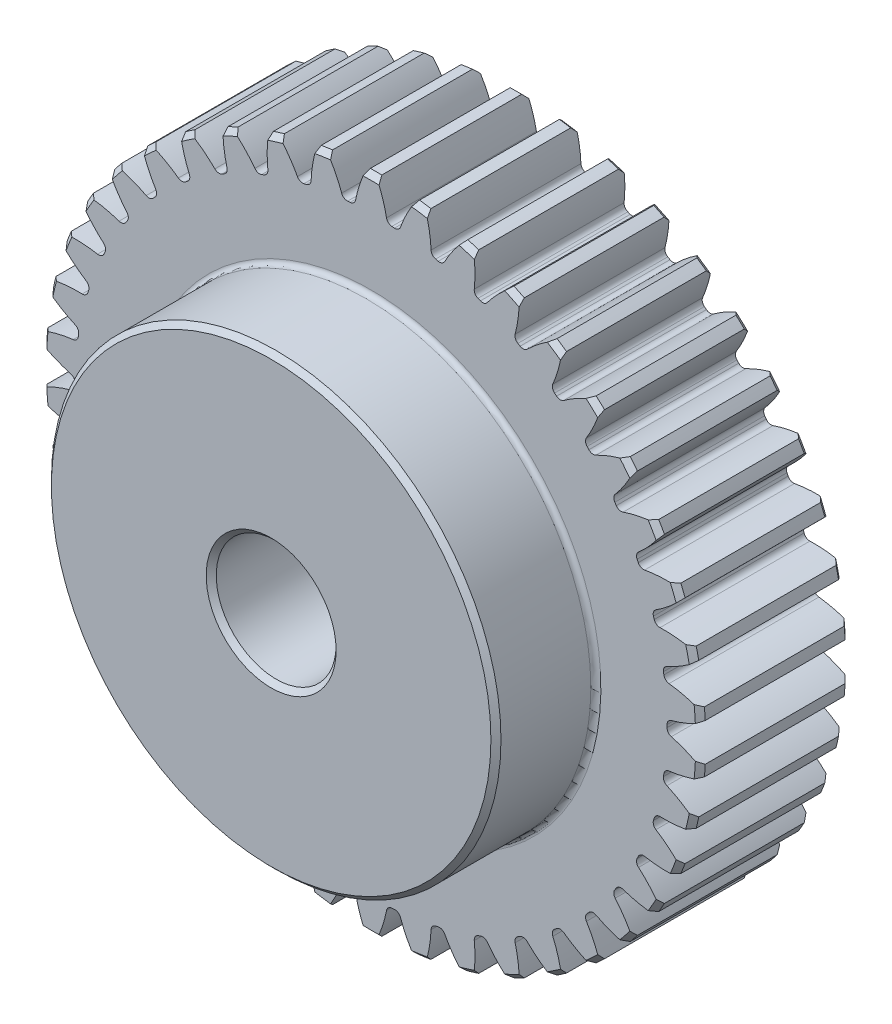
SolidWorks part; units mm, degrees
ref_plane "Front Plane" through (0, 0, 0) normal (0, 0, 1) x (1, 0, 0)
ref_plane "Top Plane" through (0, 0, 0) normal (0, 1, 0) x (1, 0, 0)
ref_plane "Right Plane" through (0, 0, 0) normal (1, 0, 0) x (0, 0, -1)
sketch "Sketch1" plane through (0, 0, 0) normal (0, 0, 1) x (1, 0, 0)
  line L0 (0, 0) -> (0, 31.5) construction
  line L1 (-10.1239, 35.1848) -> (10.1239, 27.8152) construction
  circle A0 centre (0, 0) radius 29.625 construction
  circle A1 centre (0, 0) radius 33 construction
  circle A2 centre (0, 0) radius 31.5 construction
  circle A3 centre (0, 0) radius 29.6003 construction
  circle A4 centre (0, 0) radius 22.5 construction
  circle A5 centre (0, 0) radius 6 construction
  point P8 (0.75, 0)
  point P13 (21, 0)
  dimension "OD" = 66
  dimension "Root Diameter" = 59.25
  dimension "Gear Pitch Diameter" = 63
  dimension "Base Diameter" = 59.2006
  dimension "Hub Diameter" = 45
  dimension "For Shaft Diameter" = 12
  dimension "Pressure Angle" = 20
  dimension "Number of Teeth" = 42
  dimension "Module" = 1.5
sketch "Sketch2" plane through (0, 0, 0) normal (1, 0, 0) x (0, 0, -1)
  line L0 (-10, 0) -> (15, 0) construction
  line L1 (15, 33) -> (15, -33) construction
  line L2 (0, -22.5) -> (-10, -22.5) construction
  line L3 (-10, 33) -> (15, 33) construction
  line L8 (-10, -22.5) -> (-10, 22.5) construction
  point P4 (0, 33)
  point P5 (-5, 0)
  dimension "Overall Width" = 25
  dimension "Hub Width" = 10
  dimension "Approx Set Screw Positon" = 5
  dimension "Face Width" = 15
sketch "Sketch3" plane through (0, 0, 0) normal (0, 0, 1) x (1, 0, 0)
  circle A0 centre (0, 0) radius 33
  circle A1 centre (0, 0) radius 33 construction
extrude "Boss-Extrude1" add sketch "Sketch3" against normal up to vertex (15 mm away) and the other way up to vertex (10 mm away) up to point (0, 0, -15) other way up to point (0, 0, 10)
sketch "Sketch5" plane through (0, 0, 0) normal (1, 0, 0) x (0, 0, -1)
  line L1 (0, 22.5) -> (-10, 22.5)
  line L2 (0, 22.5) -> (0, 33)
  line L3 (0, 33) -> (-10, 33)
  line L4 (-10, 22.5) -> (-10, 33)
  line L5 (-10, 0) -> (15, 0)
  line L6 (-10, 0) -> (-10, 6)
  line L7 (-10, 6) -> (15, 6)
  line L8 (15, 0) -> (15, 6)
  point P5 (0, 22.5)
  point P12 (0, 6)
revolve "Cut-Revolve1" cut sketch "Sketch5" angle 360 about L0
fillet "Fillet2" radius 0.5033 1 edges at (0, -22.5, 0)
chamfer "Chamfer1" distance 0.5033 angle 45 5 edges at (0, -6, -15) (0, -33, 0) (33, 0, -15) (0, -6, 10) (0, -22.5, 10)
sketch "Sketch4" plane through (0, 0, 0) normal (0, 0, 1) x (1, 0, 0)
  line L0 (29.6191, 0.589) -> (29.6191, -0.589)
  arc A3 (32.9456, 1.8943) -> (32.9456, -1.8943) centre (0, 0) cw
  circle A4 centre (0, 0) radius 33 construction
  arc A5 (29.6191, 0.589) -> (32.9456, 1.8943) centre (26.6987, 12.9235) ccw
  circle A8 centre (0, 0) radius 29.625 construction
  arc A9 (29.6191, -0.589) -> (32.9456, -1.8943) centre (26.6987, -12.9235) cw
  spline S0 degree 4 poles (29.5928, 0.6658) (29.5981, 0.666) (29.613, 0.6667) (29.6412, 0.6686) (29.6871, 0.6727) (29.7455, 0.6794) (29.821, 0.6896) (29.9098, 0.7037) (30.0073, 0.7214) (30.1132, 0.7431) (30.2188, 0.7668) (30.324, 0.7924) (30.4286, 0.8196) (30.5553, 0.8547) (30.707, 0.8996) (30.8839, 0.9564) (31.0842, 1.0257) (31.2878, 1.1016) (31.4878, 1.1807) (31.6893, 1.2656) (31.884, 1.3514) (32.0857, 1.4455) (32.2716, 1.5351) (32.4792, 1.6411) (32.6466, 1.7283) (32.8667, 1.8494) (32.9965, 1.9227) (33.1481, 2.0107) (33.2153, 2.0508) (33.2567, 2.0755) knots 0 0 0 0 0 0.005377 0.015084 0.028532 0.04661 0.064855 0.092111 0.119476 0.146842 0.174209 0.201575 0.228941 0.256307 0.307035 0.361767 0.4165 0.471232 0.525964 0.580697 0.635429 0.690161 0.744894 0.799626 0.854358 0.909091 0.954545 1 1 1 1 1 construction
  spline S1 degree 4 poles (29.5928, 0.6658) (29.5981, 0.666) (29.613, 0.6667) (29.6412, 0.6686) (29.6871, 0.6727) (29.7455, 0.6794) (29.821, 0.6896) (29.9098, 0.7037) (30.0073, 0.7214) (30.1132, 0.7431) (30.2188, 0.7668) (30.324, 0.7924) (30.4286, 0.8196) (30.5553, 0.8547) (30.707, 0.8996) (30.8839, 0.9564) (31.0842, 1.0257) (31.2878, 1.1016) (31.4878, 1.1807) (31.6893, 1.2656) (31.884, 1.3514) (32.0857, 1.4455) (32.2716, 1.5351) (32.4792, 1.6411) (32.6466, 1.7283) (32.819, 1.8232) (32.9028, 1.87) (32.9456, 1.8943) knots 0 0 0 0 0 0.005377 0.015084 0.028532 0.04661 0.064855 0.092111 0.119476 0.146842 0.174209 0.201575 0.228941 0.256307 0.307035 0.361767 0.4165 0.471232 0.525964 0.580697 0.635429 0.690161 0.744894 0.799626 0.854358 0.909091 0.909091 0.909091 0.909091 0.909091 construction
  spline S2 degree 4 poles (29.5928, -0.6658) (29.5981, -0.666) (29.613, -0.6667) (29.6412, -0.6686) (29.6871, -0.6727) (29.7455, -0.6794) (29.821, -0.6896) (29.9098, -0.7037) (30.0073, -0.7214) (30.1132, -0.7431) (30.2188, -0.7668) (30.324, -0.7924) (30.4286, -0.8196) (30.5553, -0.8547) (30.707, -0.8996) (30.8839, -0.9564) (31.0842, -1.0257) (31.2878, -1.1016) (31.4878, -1.1807) (31.6893, -1.2656) (31.884, -1.3514) (32.0857, -1.4455) (32.2716, -1.5351) (32.4792, -1.6411) (32.6466, -1.7283) (32.8667, -1.8494) (32.9965, -1.9227) (33.1481, -2.0107) (33.2153, -2.0508) (33.2567, -2.0755) knots 0 0 0 0 0 0.005377 0.015084 0.028532 0.04661 0.064855 0.092111 0.119476 0.146842 0.174209 0.201575 0.228941 0.256307 0.307035 0.361767 0.4165 0.471232 0.525964 0.580697 0.635429 0.690161 0.744894 0.799626 0.854358 0.909091 0.954545 1 1 1 1 1 construction
  spline S3 degree 4 poles (29.5928, -0.6658) (29.5981, -0.666) (29.613, -0.6667) (29.6412, -0.6686) (29.6871, -0.6727) (29.7455, -0.6794) (29.821, -0.6896) (29.9098, -0.7037) (30.0073, -0.7214) (30.1132, -0.7431) (30.2188, -0.7668) (30.324, -0.7924) (30.4286, -0.8196) (30.5553, -0.8547) (30.707, -0.8996) (30.8839, -0.9564) (31.0842, -1.0257) (31.2878, -1.1016) (31.4878, -1.1807) (31.6893, -1.2656) (31.884, -1.3514) (32.0857, -1.4455) (32.2716, -1.5351) (32.4792, -1.6411) (32.6466, -1.7283) (32.819, -1.8232) (32.9028, -1.87) (32.9456, -1.8943) knots 0 0 0 0 0 0.005377 0.015084 0.028532 0.04661 0.064855 0.092111 0.119476 0.146842 0.174209 0.201575 0.228941 0.256307 0.307035 0.361767 0.4165 0.471232 0.525964 0.580697 0.635429 0.690161 0.744894 0.799626 0.854358 0.909091 0.909091 0.909091 0.909091 0.909091 construction
  dimension "D1" = 1.1781
extrude "Cut-Extrude1" cut sketch "Sketch4" against normal through all both and the other way through all
fillet "Fillet1" radius 0.589 2 edges at (29.6191, 0.589, -7.5) (29.6191, -0.589, -7.5)
pattern_circular "CirPattern1" count 42 over 360 about axis through (0, 0, 0) along (0, 0, 1) of "Cut-Extrude1", "Fillet1"
equation "\"Number of Teeth\"= 42"
equation "\"Module\"= 1.5"
equation "\"Diametral Pitch\"= 1 / \"Module\""
equation "\"Dedendum\"= 1.25 / \"Diametral Pitch\""
equation "\"Pitch Diameter\"= \"Module\" * \"Number of Teeth\""
equation "\"Root Diameter\"= \"Pitch Diameter\" - ( 2 * \"Dedendum\" )"
equation "\"Root Diameter@Sketch1\"=\"Root Diameter\""
equation "\"OD@Sketch1\" = \"Outside Diameter\""
equation "\"D1@CirPattern1\"=\"Number of Teeth\""
equation "\"Pressure Angle\"=20"
equation "\"Base Diameter\"= \"Pitch Diameter\" * cos ( \"Pressure Angle\" )"
equation "\"Outside Diameter\"= ( \"Number of Teeth\" + 2 ) / \"Diametral Pitch\""
equation "\"Pitch Angle\"= 360deg / \"Number of Teeth\""
equation "\"Alpha\"= sqr ( \"Pitch Diameter\" ^ 2 - \"Base Diameter\" ^ 2 ) / \"Base Diameter\" * 180 / PI - \"Pressure Angle\""
equation "\"Beta\"= ( \"Pitch Angle\" / 4 - \"Alpha\" )"
equation "\"Phi\"= sqr ( ( \"Outside Diameter\" / 2 ) ^ 2 - ( \"Base Diameter\" / 2 ) ^ 2 ) / ( \"Base Diameter\" / 2 )"
equation "\"Addendum\"= 1 / \"Diametral Pitch\""
equation "\"WorkingDepth\"= 2 / \"Diametral Pitch\""
equation "\"WholeDepth\"= 2.25 / \"Diametral Pitch\""
equation "\"Clearance\"= 0.25 / \"Diametral Pitch\""
equation "\"ToothThickness\"= ( pi * 2 ) / \"Diametral Pitch\""
equation "\"CircularPitch\"= pi / \"Diametral Pitch\""
equation "\"Number of Teeth@Sketch1\"=\"Number of Teeth\""
equation "\"Module@Sketch1\"=\"Module\""
equation "\"Pressure Angle@Sketch1\"=\"Pressure Angle\""
equation "\"Gear Pitch Diameter@Sketch1\"=\"Pitch Diameter\""
equation "\"Base Diameter@Sketch1\"=\"Base Diameter\""
equation "\"Fillet\"= \"Clearance\" * cos ( \"Pressure Angle\" ) * tan ( ( 90 + \"Pressure Angle\" ) / 2 )"
equation "\"D1@Fillet2\"=\"Fillet\""
equation "\"Approx Set Screw Positon@Sketch2\" = \"Hub Width@Sketch2\" / 2"
equation "\"D2\"= \"Fillet\" * 2"
equation "\"D1@Chamfer1\"=\"Fillet\""
equation "\"D1@Sketch4\"=\"CircularPitch\"*0.25"
equation "\"D1@Fillet1\"=\"CircularPitch\"*0.125"
